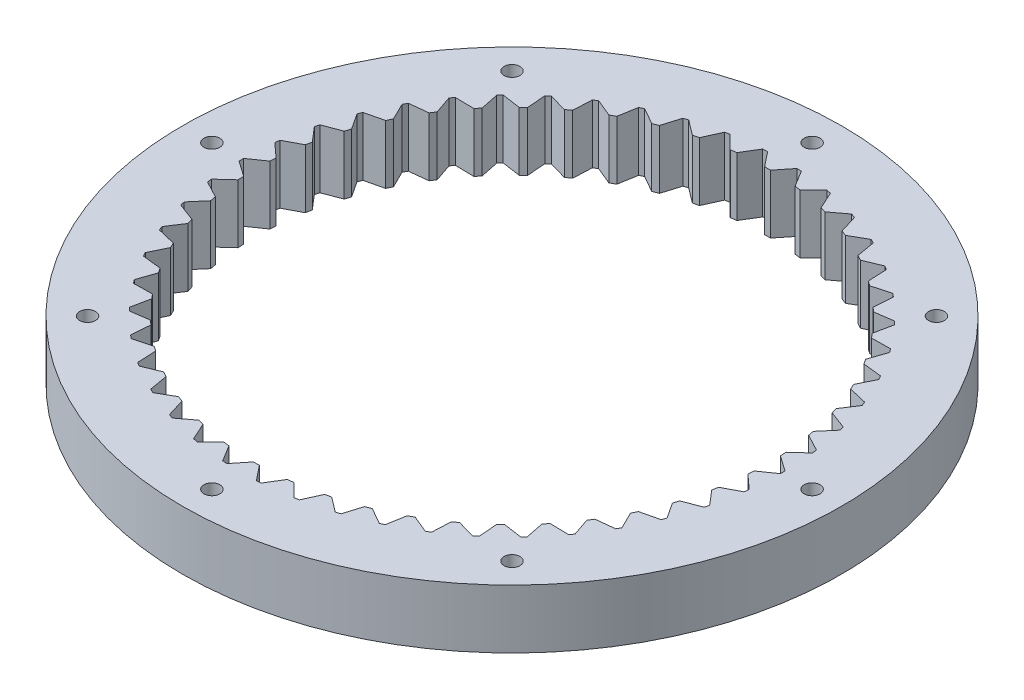
SolidWorks part; units mm, degrees
ref_plane "Front Plane" through (0, 0, 0) normal (0, 0, 1) x (1, 0, 0)
ref_plane "Top Plane" through (0, 0, 0) normal (0, 1, 0) x (1, 0, 0)
ref_plane "Right Plane" through (0, 0, 0) normal (1, 0, 0) x (0, 0, -1)
sketch "Sketch1" plane through (0, 0, 0) normal (0, 1, 0) x (1, 0, 0)
  circle A0 centre (0, 0) radius 46
  circle A1 centre (0, 0) radius 56
  dimension "D1" = 92
  dimension "D2" = 10
extrude "MainBody" add sketch "Sketch1" along normal blind 10
sketch "Sketch2" plane through (0, 0, 0) normal (0, 1, 0) x (1, 0, 0)
  line L0 (0, 45.932) -> (0, 48.432) construction
  line L1 (0.5, 48.432) -> (-0.5, 48.432)
  line L2 (-0.5, 48.432) -> (-2.5, 45.932)
  line L5 (0.5, 48.432) -> (2.5, 45.932)
  line L6 (-2.5, 45.932) -> (2.5, 45.932)
  line L7 (0.5, 43.432) -> (2.5, 45.932)
  line L8 (-0.5, 43.432) -> (-2.5, 45.932)
  line L9 (0.5, 43.432) -> (-0.5, 43.432)
  circle A2 centre (0, 0) radius 46 construction
  circle A3 centre (0, 0) radius 46 construction
  dimension "D1" = 0.5
  dimension "D2" = 2.5
  dimension "D3" = 2.5
extrude "SingleTooth" add sketch "Sketch2" along normal blind 10 contours L9 L7 L6 L8 | L2 L6 L5 L1
pattern_circular "ToothPattern" count 50 over 360 about axis through (0, 0, 0) along (0, 1, 0) of "SingleTooth"
sketch "Sketch3" plane through (0, 10, 0) normal (0, 1, 0) x (1, 0, 0)
  circle A0 centre (0, 0) radius 56 construction
  circle A1 centre (0, 0) radius 56 construction
  circle A2 centre (0, 0) radius 51 construction
  circle A3 centre (-51, 0) radius 1.35
  circle A4 centre (-36.0624, 36.0624) radius 1.35
  circle A5 centre (0, 51) radius 1.35
  circle A6 centre (36.0624, 36.0624) radius 1.35
  circle A7 centre (51, 0) radius 1.35
  circle A8 centre (36.0624, -36.0624) radius 1.35
  circle A9 centre (0, -51) radius 1.35
  circle A10 centre (-36.0624, -36.0624) radius 1.35
  point P7 (0, 0)
  point P23 (0, 0)
  dimension "D2" = 2.7
  dimension "D1" = 5
  dimension "D3" = 8
extrude "Cut-Extrude1" cut sketch "Sketch3" against normal through all
